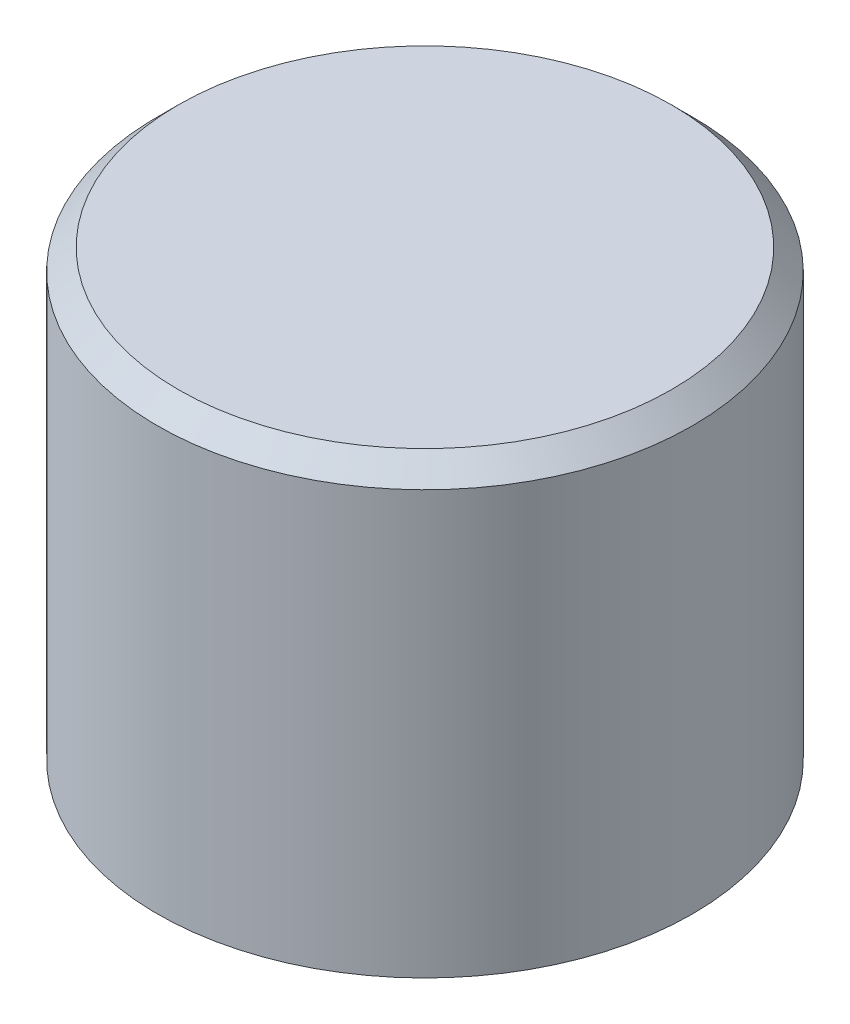
SolidWorks part; units mm, degrees
ref_plane "Спереди" through (0, 0, 0) normal (0, 0, 1) x (1, 0, 0)
ref_plane "Сверху" through (0, 0, 0) normal (0, 1, 0) x (1, 0, 0)
ref_plane "Справа" through (0, 0, 0) normal (1, 0, 0) x (0, 0, -1)
sketch "Эскиз1" plane through (0, 0, 0) normal (0, 0, 1) x (1, 0, 0)
  line L0 (-2.5, 5.5) -> (-2.5, 15)
  line L1 (-2.5, 15) -> (0, 15)
  line L2 (0, 15) -> (0, 17)
  line L3 (0, 17) -> (-10.25, 17)
  line L4 (-10.25, 17) -> (-10.25, 0)
  line L5 (-10.25, 0) -> (-9.85, 0)
  line L6 (-9.85, 0) -> (-9.85, 5.5)
  line L7 (-9.85, 5.5) -> (-2.5, 5.5)
  point P0 (-2.5, 13.5741)
  point P7 (-4.7845, -1.2596)
  dimension "D1" = 10.25
  dimension "D2" = 9.85
  dimension "D3" = 5.5
  dimension "D4" = 2.5
  dimension "D5" = 17
  dimension "D6" = 15
revolve "Повернуть1" add sketch "Эскиз1" angle 360 about L2
chamfer "Фаска1" distance 0.8 angle 45 1 edges at (10.25, 17, 0)
